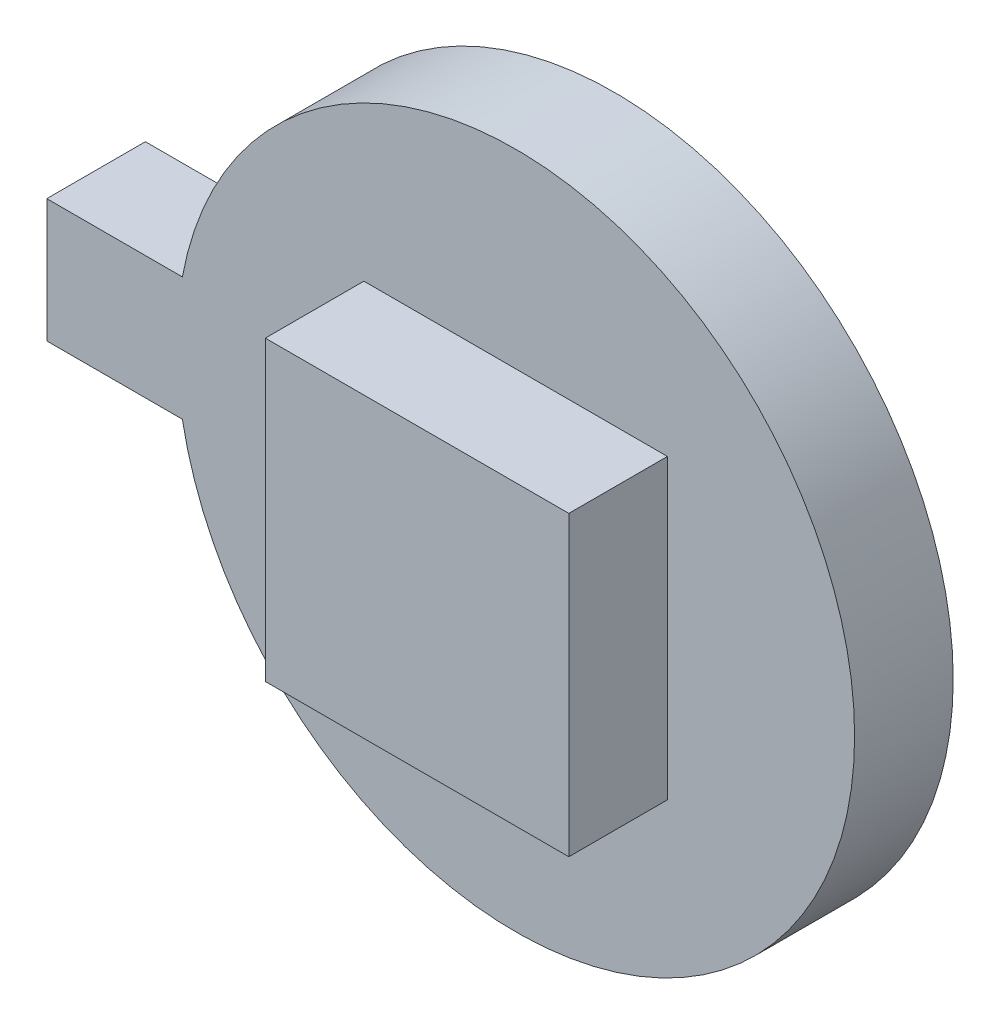
SolidWorks part; units mm, degrees
ref_plane "前视基准面" through (0, 0, 0) normal (0, 0, 1) x (1, 0, 0)
ref_plane "上视基准面" through (0, 0, 0) normal (0, 1, 0) x (1, 0, 0)
ref_plane "右视基准面" through (0, 0, 0) normal (1, 0, 0) x (0, 0, -1)
other "Configuration Table"
sketch "草图1" plane through (0, 0, 0) normal (0, 0, 1) x (1, 0, 0)
  line L0 (-14.2852, 0) -> (12.1122, 0) construction
  line L1 (-5.4083, 1) -> (-7.6083, 1)
  line L2 (-7.6083, 1) -> (-7.6083, -1)
  line L3 (-5.4083, -1) -> (-7.6083, -1)
  arc A0 (-5.4083, -1) -> (-5.4083, 1) centre (0, 0) ccw
  point P10 (-7.6083, 0)
  dimension "D1" = 11
  dimension "D2" = 2.2
  dimension "D3" = 2
extrude "凸台-拉伸1" add sketch "草图1" along normal blind 1.6
sketch "草图2" plane through (0, 0, 1.6) normal (0, 0, 1) x (1, 0, 0)
  line L1 (-2.4628, -2.4127) -> (2.4628, -2.4127)
  line L2 (-2.4628, -2.4127) -> (-2.4628, 2.4127)
  line L3 (-2.4628, 2.4127) -> (2.4628, 2.4127)
  line L4 (2.4628, -2.4127) -> (2.4628, 2.4127)
  line L5 (-2.4628, -2.4127) -> (2.4628, 2.4127) construction
  line L6 (-2.4628, 2.4127) -> (2.4628, -2.4127) construction
  point P0 (0, 0)
extrude "凸台-拉伸2" add sketch "草图2" along normal blind 1.6
